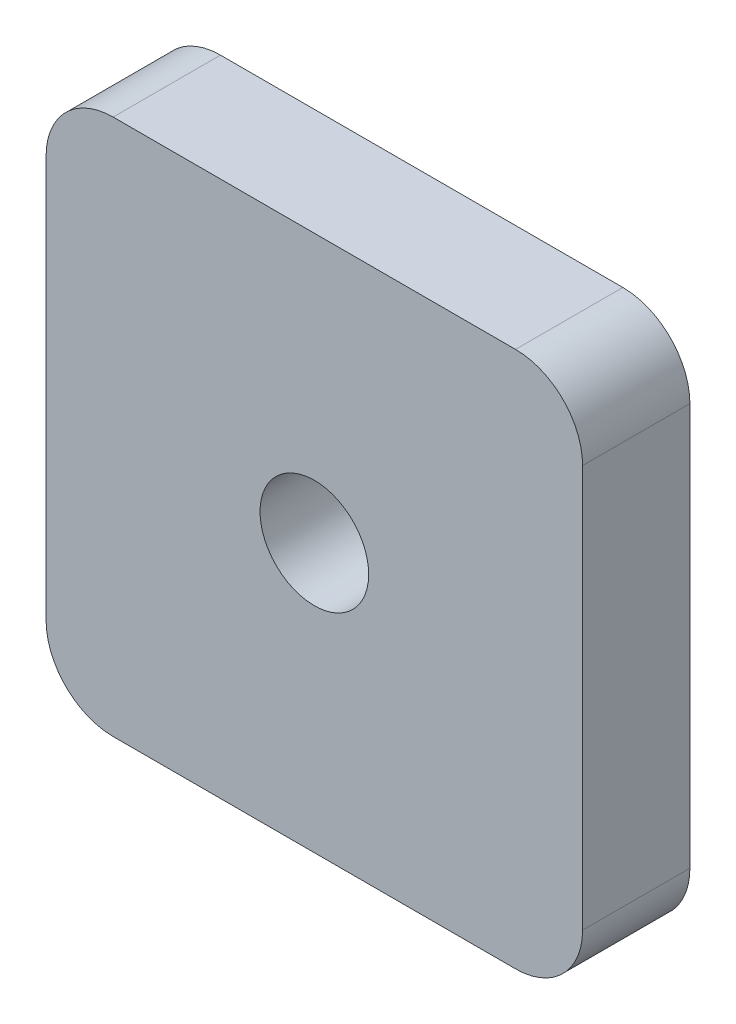
SolidWorks part; units mm, degrees
ref_plane "Front Plane" through (0, 0, 0) normal (0, 0, 1) x (1, 0, 0)
ref_plane "Top Plane" through (0, 0, 0) normal (0, 1, 0) x (1, 0, 0)
ref_plane "Right Plane" through (0, 0, 0) normal (1, 0, 0) x (0, 0, -1)
sketch "Sketch1" plane through (0, 0, 0) normal (0, 0, 1) x (1, 0, 0)
  line L1 (-20, 20) -> (20, 20)
  line L2 (-20, 20) -> (-20, -20)
  line L3 (-20, -20) -> (20, -20)
  line L4 (20, 20) -> (20, -20)
  line L5 (-20, 20) -> (20, -20) construction
  line L6 (-20, -20) -> (20, 20) construction
  circle A0 centre (0, 0) radius 4.05
  point P0 (0, 0)
  dimension "D3" = 8.1
  dimension "D1" = 40
  dimension "D2" = 40
extrude "Boss-Extrude1" add sketch "Sketch1" along normal blind 8
fillet "Fillet1" radius 5 4 edges at (20, -20, 4) (-20, -20, 4) (-20, 20, 4) (20, 20, 4)
